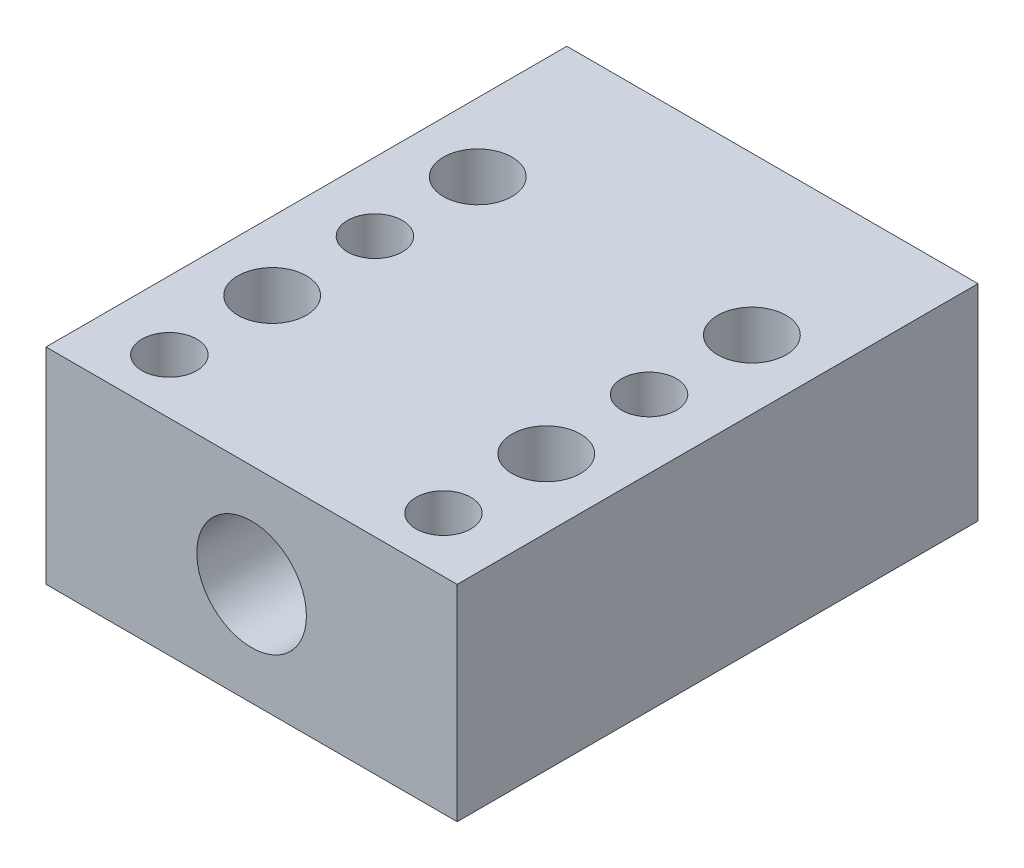
SolidWorks part; units mm, degrees
ref_plane "前视基准面" through (0, 0, 0) normal (0, 0, 1) x (1, 0, 0)
ref_plane "上视基准面" through (0, 0, 0) normal (0, 1, 0) x (1, 0, 0)
ref_plane "右视基准面" through (0, 0, 0) normal (1, 0, 0) x (0, 0, -1)
sketch "草图1" plane through (0, 0, 0) normal (0, 0, 1) x (1, 0, 0)
  line L1 (-15, 7.5) -> (15, 7.5)
  line L2 (-15, 7.5) -> (-15, -7.5)
  line L3 (-15, -7.5) -> (15, -7.5)
  line L4 (15, 7.5) -> (15, -7.5)
  line L5 (-15, 7.5) -> (15, -7.5) construction
  line L6 (-15, -7.5) -> (15, 7.5) construction
  circle A0 centre (0, 0) radius 4
  point P0 (0, 0)
  dimension "D3" = 8
  dimension "D1" = 30
  dimension "D2" = 15
extrude "凸台-拉伸1" add sketch "草图1" along normal blind 38
sketch "草图2" plane through (0, 7.5, 0) normal (0, 1, 0) x (1, 0, 0)
  line L0 (-15, 0) -> (15, -38) construction
  line L1 (15, 0) -> (-15, -38) construction
  line L2 (15, -19) -> (-15, -19) construction
  line L3 (-15, -38) -> (-15, 0) construction
  line L4 (15, -38) -> (15, 0) construction
  line L5 (-10, -19) -> (-10, 0) construction
  line L6 (15, 0) -> (-15, 0) construction
  line L7 (-10, -19) -> (-10, -38) construction
  line L8 (15, -38) -> (-15, -38) construction
  line L9 (10, -38) -> (10, 0) construction
  circle A0 centre (10, -19) radius 2
  circle A1 centre (-10, -19) radius 2
  circle A2 centre (10, -26.5) radius 2.5
  circle A3 centre (-10, -26.5) radius 2.5
  circle A4 centre (-10, -34) radius 2
  circle A5 centre (10, -34) radius 2
  circle A6 centre (10, -11.5) radius 2.5
  circle A7 centre (-10, -11.5) radius 2.5
  point P18 (0, -19)
  dimension "D3" = 4
  dimension "D4" = 4
  dimension "D7" = 5
  dimension "D8" = 5
  dimension "D11" = 4
  dimension "D12" = 4
  dimension "D13" = 5
  dimension "D14" = 5
  dimension "D15" = 7.5
  dimension "D1" = 20
  dimension "D2" = 10
  dimension "D5" = 7.5
  dimension "D6" = 7.5
  dimension "D9" = 7.5
  dimension "D10" = 7.5
  dimension "D16" = 7.5
extrude "切除-拉伸1" cut sketch "草图2" against normal blind 6
